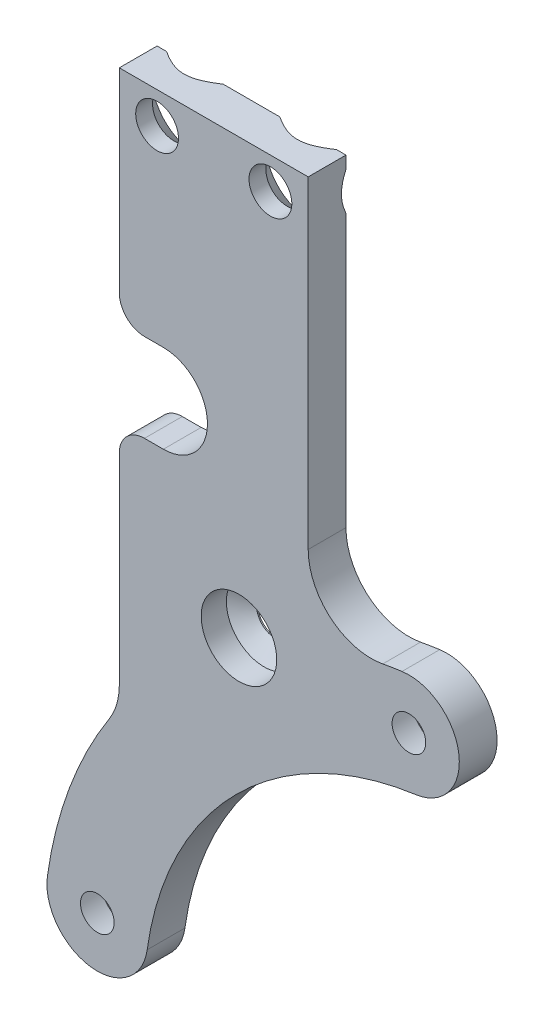
SolidWorks part; units mm, degrees
ref_plane "Plano frontal" through (0, 0, 0) normal (0, 0, 1) x (1, 0, 0)
ref_plane "Plano superior" through (0, 0, 0) normal (0, 1, 0) x (1, 0, 0)
ref_plane "Plano direito" through (0, 0, 0) normal (1, 0, 0) x (0, 0, -1)
sketch "Esboço1" plane through (0, 0, 0) normal (0, 0, 1) x (1, 0, 0)
  line L3 (0, 0) -> (70.5648, 0) construction
  line L4 (0, 0) -> (0, -13.7007) construction
  line L5 (-12, 30.7684) -> (-12, 63)
  line L6 (-12, 63) -> (-27, 63)
  line L7 (-27, 63) -> (-27, 19.0183)
  line L8 (-32.7106, 4.5512) -> (0, 0) construction
  line L9 (0, 0) -> (-4.5512, 32.7106) construction
  arc A0 (-27, 19.0183) -> (-32.7106, 4.5512) centre (0, 0) ccw
  arc A1 (-12, 30.7684) -> (-4.5512, 32.7106) centre (0, 0) cw
  arc A2 (-24.7869, 3.4488) -> (-3.4488, 24.7869) centre (0, 0) cw
  arc A3 (-24.7869, 3.4488) -> (-32.7106, 4.5512) centre (-28.7487, 4) cw
  arc A4 (-3.4488, 24.7869) -> (-4.5512, 32.7106) centre (-4, 28.7487) ccw
  dimension "D2" = 4
  dimension "D3" = 4
  dimension "D6" = 27
  dimension "D1" = 15
  dimension "D4" = 35
  dimension "D5" = 63
extrude "Ressalto-extrusão1" add sketch "Esboço1" along normal blind 3
hole_wizard "Broca de rosquear para tarraxa de M31" positions "Esboço2" profile "Esboço3" hole size "M3" standard "ISO" end condition up to next
sketch "Esboço2" plane through (0, 0, 3) normal (0, 0, 1) x (1, 0, 0)
  point P9 (-28.7487, 4)
  point P12 (-4, 28.7487)
sketch "Esboço3" plane through (-28.7487, 4, 3) normal (1, 0, 0) x (0, -1, 0)
  line L0 (0, 0) -> (0, 3)
  line L1 (0, 3) -> (1.25, 3)
  line L2 (1.25, 3) -> (1.25, 0)
  line L5 (1.25, 0) -> (0, 0)
  line L11 (0, -6.35) -> (0, 107.95) construction
  dimension "Thru Hole Dia." = 2.5
  dimension "Thru Hole Depth" = 3
hole_wizard "Furo de diâmetro Ø6.0 (6)1" positions "Esboço4" profile "Esboço6" hole size "Ø6.0" standard "ISO"
sketch "Esboço4" plane through (0, 0, 0) normal (0, 0, -1) x (-1, 0, 0)
  point P5 (28.7487, 4)
  point P8 (4, 28.7487)
sketch "Esboço6" plane through (-28.7487, 4, 0) normal (1, 0, 0) x (0, 1, 0)
  line L0 (0, 0) -> (0, 3.8026)
  line L1 (0, 3.8026) -> (3, 2)
  line L2 (3, 2) -> (3, 0)
  line L5 (3, 0) -> (0, 0)
  line L10 (0, 3.8026) -> (-3, 2) construction
  line L11 (0, -6.35) -> (0, 107.95) construction
  dimension "Hole Dia." = 6
  dimension "Hole Depth" = 2
  dimension "Drill Angle" = 118
hole_wizard "Escareado para SFHCS M31" positions "Esboço7" profile "Esboço9" countersink size "M3" standard "Ansi Metric"
sketch "Esboço7" plane through (0, 0, 0) normal (0, 0, -1) x (-1, 0, 0)
  line L3 (12, 63) -> (27, 63) construction
  line L5 (12, 30.7684) -> (12, 63) construction
  line L6 (27, 63) -> (27, 19.0183) construction
  point P0 (15, 60.5)
  point P2 (24, 60.5)
  dimension "D1" = 2.5
  dimension "D2" = 3
  dimension "D3" = 3
  dimension "D4" = 2.5
sketch "Esboço9" plane through (-15, 60.5, 0) normal (1, 0, 0) x (0, 1, 0)
  line L0 (0, 0) -> (0, 11.0215)
  line L1 (0, 11.0215) -> (1.7, 10)
  line L2 (1.7, 10) -> (1.7, 1.66)
  line L3 (1.7, 1.66) -> (3.36, 0)
  line L5 (3.36, 0) -> (0, 0)
  line L6 (-1.7, 1.66) -> (-3.36, 0) construction
  line L10 (0, 11.0215) -> (-1.7, 10) construction
  line L11 (0, -6.35) -> (0, 107.95) construction
  dimension "Hole Dia." = 3.4
  dimension "Hole Depth" = 10
  dimension "Near C'Sink Dia." = 6.72
  dimension "Near C'Sink Angle" = 90
  dimension "Drill Angle" = 118
sketch "Esboço10" plane through (0, 0, 0) normal (0, 0, -1) x (-1, 0, 0)
  line L1 (23.5, 45.5183) -> (27, 45.5183)
  line L2 (23.5, 38.5183) -> (27, 38.5183)
  line L3 (27, 45.5183) -> (27, 38.5183)
  line L4 (27, 58.9869) -> (27, 19.0183) construction
  arc A0 (23.5, 45.5183) -> (23.5, 38.5183) centre (23.5, 42.0183) ccw
  circle A1 centre (17.4985, 28.5445) radius 1.5
  circle A2 centre (4, 28.7487) radius 1.3357 construction
  dimension "D1" = 23
  dimension "D2" = 3.5
  dimension "D3" = 7
  dimension "D6" = 3
  dimension "D5" = 13.5
  dimension "D4" = 14.75
extrude "Corte-extrusão1" cut sketch "Esboço10" against normal through all
fillet "Filete1" radius 2 2 edges at (-27, 45.5183, 1.5) (-27, 38.5183, 1.5)
fillet "Filete2" radius 5 2 edges at (-27, 19.0183, 1.5) (-12, 30.7684, 1.5)
hole_wizard "Furo de diâmetro Ø6.0 (6)2" positions "Esboço11" profile "Esboço13" hole size "Ø6.0" standard "ISO"
sketch "Esboço11" plane through (0, 0, 3) normal (0, 0, 1) x (1, 0, 0)
  point P0 (-17.4985, 28.5445)
sketch "Esboço13" plane through (-17.4985, 28.5445, 3) normal (1, 0, 0) x (0, -1, 0)
  line L0 (0, 0) -> (0, 3.8026)
  line L1 (0, 3.8026) -> (3, 2)
  line L2 (3, 2) -> (3, 0)
  line L5 (3, 0) -> (0, 0)
  line L10 (0, 3.8026) -> (-3, 2) construction
  line L11 (0, -6.35) -> (0, 107.95) construction
  dimension "Hole Dia." = 6
  dimension "Hole Depth" = 2
  dimension "Drill Angle" = 118
